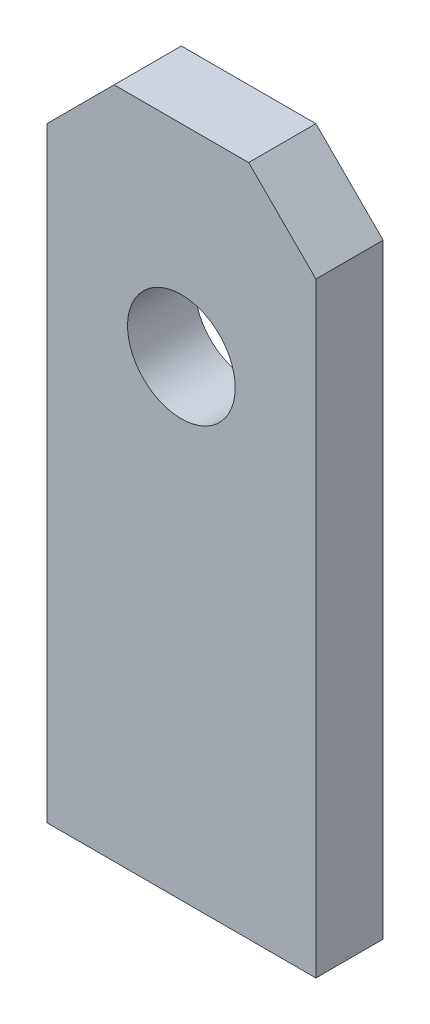
SolidWorks part; units mm, degrees
material "ASTM A36 Steel"
ref_plane "Front Plane" through (0, 0, 0) normal (0, 0, 1) x (1, 0, 0)
ref_plane "Top Plane" through (0, 0, 0) normal (0, 1, 0) x (1, 0, 0)
ref_plane "Right Plane" through (0, 0, 0) normal (1, 0, 0) x (0, 0, -1)
sketch "Sketch1" plane through (0, 0, 0) normal (0, 0, 1) x (1, 0, 0)
  line L0 (-20, -50) -> (20, -50)
  line L1 (20, -50) -> (20, 40)
  line L2 (20, 40) -> (10, 50)
  line L3 (10, 50) -> (-10, 50)
  line L4 (-10, 50) -> (-20, 40)
  line L5 (-20, 40) -> (-20, -50)
  circle A0 centre (0, 20) radius 8
  point P2 (0, 50)
  dimension "D8" = 70
  dimension "D9" = 16
  dimension "D1" = 40
  dimension "D2" = 100
  dimension "D3" = 20
  dimension "D4" = 45
  dimension "D5" = 45
  dimension "D6" = 10
  dimension "D7" = 50
extrude "Boss-Extrude1" add sketch "Sketch1" along normal mid plane 10
